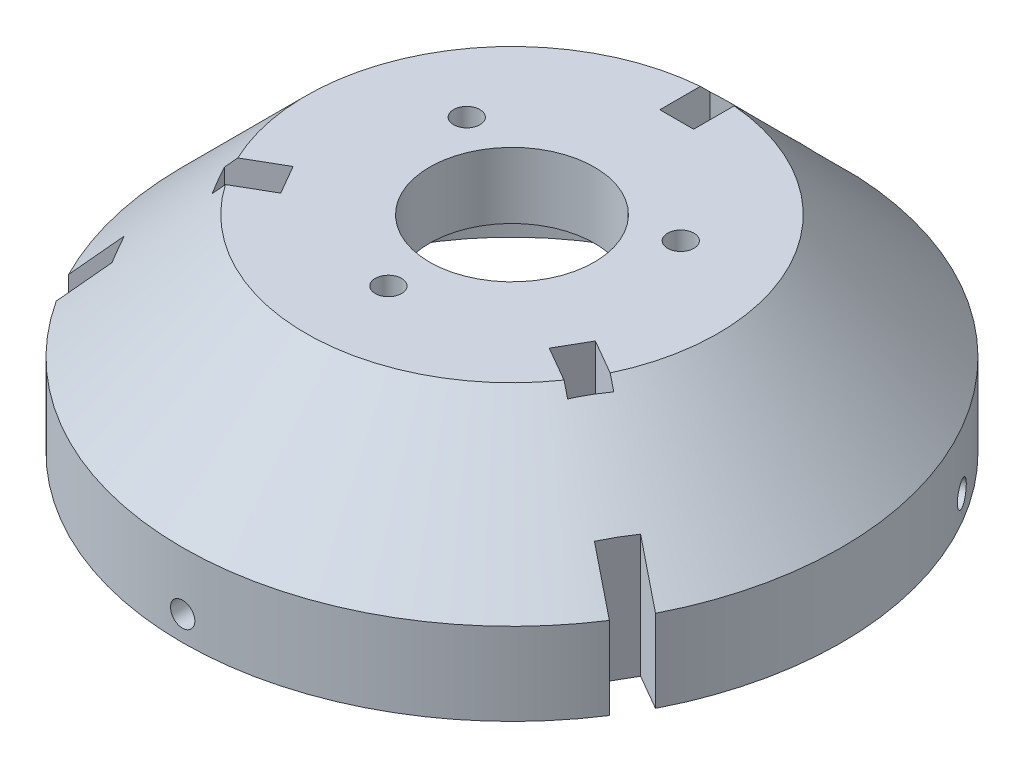
SolidWorks part; units mm, degrees
material "PE 低/中密度"
ref_plane "前视基准面" through (0, 0, 0) normal (0, 0, 1) x (1, 0, 0)
ref_plane "上视基准面" through (0, 0, 0) normal (0, 1, 0) x (1, 0, 0)
ref_plane "右视基准面" through (0, 0, 0) normal (1, 0, 0) x (0, 0, -1)
other "Configuration Table"
sketch "草图1" plane through (0, 0, 0) normal (1, 0, 0) x (0, 0, -1)
  line L0 (0, 0) -> (0, 25) construction
  line L1 (0, 25) -> (-25, 25)
  line L2 (-25, 25) -> (-40, 10)
  line L3 (-40, 10) -> (-40, 0)
  line L4 (-40, 0) -> (-32, 0)
  line L5 (-32, 0) -> (-32, 6.6863)
  line L6 (-32, 6.6863) -> (-21.6863, 17)
  line L7 (-21.6863, 17) -> (0, 17)
  line L8 (0, 17) -> (0, 25)
  line L9 (-32, 0) -> (0, 0) construction
  dimension "D1" = 25
  dimension "D2" = 25
  dimension "D3" = 40
  dimension "D4" = 10
  dimension "D5" = 8
  dimension "D6" = 8
  dimension "D7" = 8
revolve "旋转1" add sketch "草图1" angle 360 about L0
sketch "草图2" plane through (0, 25, 0) normal (0, 1, 0) x (1, 0, 0)
  line L0 (0, 0) -> (0, 38.05) construction
  line L1 (0, 0) -> (12.9904, 7.5) construction
  line L2 (36.6186, -18.7746) -> (31.3359, -15.7246)
  line L3 (-2.05, 20) -> (2.05, 20)
  line L4 (-2.05, 20) -> (-2.05, 26.1)
  line L5 (-2.05, 26.1) -> (2.05, 26.1)
  line L6 (2.05, 20) -> (2.05, 26.1)
  line L7 (-2.05, 20) -> (2.05, 26.1) construction
  line L8 (-2.05, 26.1) -> (2.05, 20) construction
  line L9 (-2.05, 41.1) -> (2.05, 41.1)
  line L10 (-2.05, 41.1) -> (-2.05, 35)
  line L11 (-2.05, 35) -> (2.05, 35)
  line L12 (2.05, 41.1) -> (2.05, 35)
  line L13 (-2.05, 41.1) -> (2.05, 35) construction
  line L14 (-2.05, 35) -> (2.05, 41.1) construction
  line L15 (36.6186, -18.7746) -> (34.5686, -22.3254)
  line L16 (34.5686, -22.3254) -> (29.2859, -19.2754)
  line L17 (31.3359, -15.7246) -> (29.2859, -19.2754)
  line L18 (18.3455, -8.2246) -> (23.6283, -11.2746)
  line L19 (18.3455, -8.2246) -> (16.2955, -11.7754)
  line L20 (16.2955, -11.7754) -> (21.5783, -14.8254)
  line L21 (23.6283, -11.2746) -> (21.5783, -14.8254)
  line L22 (-34.5686, -22.3254) -> (-29.2859, -19.2754)
  line L23 (-34.5686, -22.3254) -> (-36.6186, -18.7746)
  line L24 (-36.6186, -18.7746) -> (-31.3359, -15.7246)
  line L25 (-29.2859, -19.2754) -> (-31.3359, -15.7246)
  line L26 (-16.2955, -11.7754) -> (-21.5783, -14.8254)
  line L27 (-16.2955, -11.7754) -> (-18.3455, -8.2246)
  line L28 (-18.3455, -8.2246) -> (-23.6283, -11.2746)
  line L29 (-21.5783, -14.8254) -> (-23.6283, -11.2746)
  circle A0 centre (0, 0) radius 10
  circle A2 centre (12.9904, 7.5) radius 1.6
  circle A3 centre (0, -15) radius 1.6
  circle A4 centre (-12.9904, 7.5) radius 1.6
  point P9 (0, 23.05)
  point P39 (0, 0)
  dimension "D2" = 20
  dimension "D3" = 3.2
  dimension "D1" = 60
  dimension "D4" = 15
  dimension "D5" = 4.1
  dimension "D6" = 4.1
  dimension "D7" = 6.1
  dimension "D8" = 6.1
  dimension "D9" = 35
  dimension "D10" = 20
  dimension "D11" = 3
extrude "切除-拉伸1" cut sketch "草图2" against normal blind 42
ref_plane "基准面2" through (0, 0, 40) normal (0, 0, 1) x (1, 0, 0)
sketch "草图3" plane through (0, 0, 40) normal (0, 0, 1) x (1, 0, 0)
  line L0 (0, 0) -> (0, 3) construction
  line L1 (-33.5705, 0) -> (33.5705, 0) construction
  circle A0 centre (0, 3) radius 1.475
  dimension "D1" = 2.95
  dimension "D2" = 3
extrude "切除-拉伸2" cut sketch "草图3" against normal blind 15 contours A0
cosmetic thread "装饰螺纹线1" parameters "D2"=3.95
pattern_circular "阵列(圆周)1" count 3 every 120 about axis through (0, 10, 0) along (0, -1, 0) of "切除-拉伸2"
